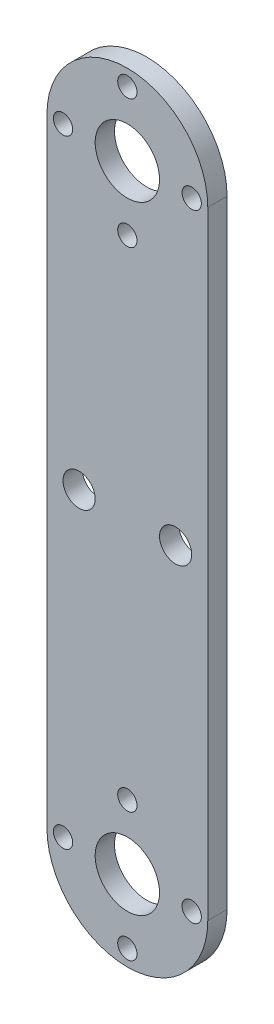
SolidWorks part; units mm, degrees
ref_plane "Front Plane" through (0, 0, 0) normal (0, 0, 1) x (1, 0, 0)
ref_plane "Top Plane" through (0, 0, 0) normal (0, 1, 0) x (1, 0, 0)
ref_plane "Right Plane" through (0, 0, 0) normal (1, 0, 0) x (0, 0, -1)
sketch "Sketch1" plane through (0, 0, 0) normal (0, 0, 1) x (1, 0, 0)
  line L0 (0, 4.8) -> (0.5, 4.8) construction
  line L2 (0, 0) -> (0, 9.6)
  line L4 (2.5, 0) -> (2.5, 9.6)
  line L5 (2.5, 4.8) -> (2, 4.8) construction
  arc A0 (0, 9.6) -> (2.5, 9.6) centre (1.25, 9.6) cw
  arc A1 (0, 0) -> (2.5, 0) centre (1.25, 0) ccw
  circle A2 centre (1.25, 9.6) radius 0.5
  circle A3 centre (1.25, 0) radius 0.5
  circle A4 centre (0.5, 4.8) radius 0.25
  circle A5 centre (2, 4.8) radius 0.25
  dimension "D3" = 1
  dimension "D4" = 1
  dimension "D7" = 0.5
  dimension "D8" = 0.5
  dimension "D1" = 2.5
  dimension "D2" = 9.6
  dimension "D5" = 0.5
  dimension "D6" = 0.5
extrude "Boss-Extrude2" add sketch "Sketch1" along normal blind 0.3
ref_plane "Plane1" through (0, 0, 0.3) normal (0, 0, 1) x (1, 0, 0)
sketch "Sketch2" plane through (0, 0, 0.3) normal (0, 0, 1) x (1, 0, 0)
  circle A0 centre (1.25, 9.6) radius 1
  circle A1 centre (0.25, 9.6) radius 0.15
  dimension "D1" = 2
  dimension "D2" = 0.3
extrude "Cut-Extrude1" cut sketch "Sketch2" against normal blind 10 contours A0 A1 | A0 A1
pattern_circular "CirPattern2" count 4 every 90 about axis through (1.25, 9.6, 0) along (0, 0, 1) of "Cut-Extrude1"
sketch "Sketch3" plane through (0, 0, 0.3) normal (0, 0, 1) x (1, 0, 0)
  circle A0 centre (1.25, 0) radius 1
  circle A1 centre (2.25, 0) radius 0.15
  dimension "D1" = 2
  dimension "D2" = 0.3
extrude "Cut-Extrude2" cut sketch "Sketch3" against normal blind 10 contours A0 A1 | A0 A1
pattern_circular "CirPattern3" count 4 every 90 about axis through (1.25, 0, 0) along (0, 0, 1) of "Cut-Extrude2"
